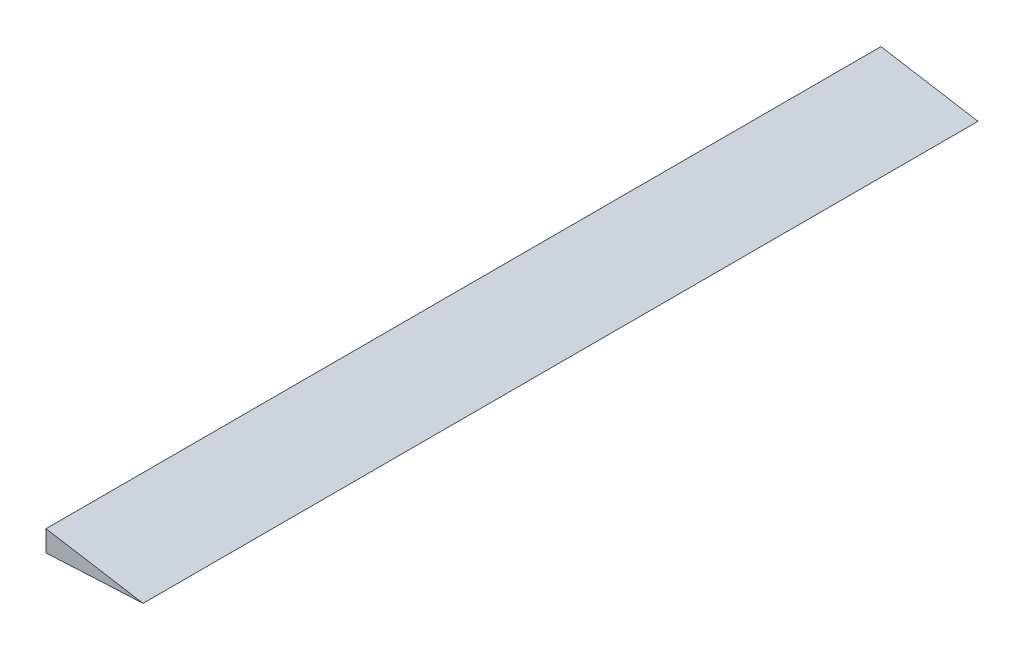
SolidWorks part; units mm, degrees
material "Balsa"
ref_plane "Front Plane" through (0, 0, 0) normal (0, 0, 1) x (1, 0, 0)
ref_plane "Top Plane" through (0, 0, 0) normal (0, 1, 0) x (1, 0, 0)
ref_plane "Right Plane" through (0, 0, 0) normal (1, 0, 0) x (0, 0, -1)
sketch "Sketch1" plane through (0, 0, 0) normal (0, 0, 1) x (1, 0, 0)
  line L0 (306.8496, -2.5161) -> (306.8496, 8.4499) construction
  line L1 (306.8496, -2.5161) -> (306.8496, 8.4499)
  line L2 (306.8496, 8.4499) -> (357.6496, 0)
  line L3 (306.8496, -2.5161) -> (357.6496, 0)
  spline S0 degree 3 poles (354.9573, 0.0431) (358.3317, -0.0432) (354.9981, 0.2938) (352.3707, 0.8024) (346.1763, 1.8676) (338.7813, 3.2655) (329.3081, 4.8919) (318.2482, 6.6648) (305.5952, 8.6507) (291.564, 10.8193) (276.34, 13.1505) (260.1392, 15.5903) (243.1815, 18.0913) (225.699, 20.6027) (207.9209, 23.0318) (190.087, 25.3152) (172.4086, 27.3328) (155.0467, 28.9096) (138.1258, 29.947) (121.7437, 30.3922) (105.9899, 30.2108) (90.9433, 29.4155) (76.6903, 28.0308) (63.3272, 26.1868) (50.9728, 23.9485) (39.7523, 21.3791) (29.7714, 18.545) (21.1318, 15.5018) (13.8914, 12.3237) (8.1391, 9.1075) (3.8158, 5.9031) (1.1802, 2.9693) (-0.4877, -0.018) (1.2572, -2.9285) (4.805, -4.6528) (9.8754, -6.6365) (16.78, -8.2511) (25.3535, -9.7017) (35.5828, -10.8813) (47.3622, -11.8027) (60.5842, -12.4624) (75.1117, -12.8607) (90.7897, -13.0132) (107.4435, -12.9137) (124.9052, -12.5651) (143.0256, -11.8868) (161.6617, -10.9405) (180.6424, -9.8572) (199.7442, -8.7119) (218.721, -7.5525) (237.3263, -6.4253) (255.3201, -5.3536) (272.4652, -4.367) (288.5372, -3.4753) (303.3148, -2.6922) (316.6121, -2.0207) (328.2104, -1.4385) (338.1246, -0.9102) (345.8395, -0.4061) (352.2525, -0.129) (354.9573, 0.0431) (358.3317, -0.0432) (354.9981, 0.2938) knots -0.015092 -0.006889 -0.001754 0 0.001748 0.006827 0.01488 0.025572 0.038694 0.054171 0.071834 0.091435 0.112685 0.135293 0.158944 0.183315 0.20807 0.232879 0.257399 0.281384 0.304706 0.327241 0.348897 0.369607 0.389308 0.407886 0.425177 0.441027 0.4553 0.467904 0.478752 0.487814 0.49509 0.500617 0.504451 0.507804 0.513091 0.520546 0.530249 0.542214 0.556382 0.572656 0.590895 0.610925 0.632536 0.655496 0.679547 0.704499 0.730211 0.756436 0.782837 0.809062 0.834776 0.859641 0.883338 0.905541 0.925965 0.944326 0.960366 0.973929 0.984908 0.993111 0.998246 1 1.001748 1.006827 1.01488 only from (357.6496, 0) to (357.6496, 0) construction
  spline S1 degree 3 poles (354.9573, 0.0431) (358.3317, -0.0432) (354.9981, 0.2938) (352.3707, 0.8024) (346.1763, 1.8676) (338.7813, 3.2655) (329.3081, 4.8919) (318.2482, 6.6648) (305.5952, 8.6507) (291.564, 10.8193) (276.34, 13.1505) (260.1392, 15.5903) (243.1815, 18.0913) (225.699, 20.6027) (207.9209, 23.0318) (190.087, 25.3152) (172.4086, 27.3328) (155.0467, 28.9096) (138.1258, 29.947) (121.7437, 30.3922) (105.9899, 30.2108) (90.9433, 29.4155) (76.6903, 28.0308) (63.3272, 26.1868) (50.9728, 23.9485) (39.7523, 21.3791) (29.7714, 18.545) (21.1318, 15.5018) (13.8914, 12.3237) (8.1391, 9.1075) (3.8158, 5.9031) (1.1802, 2.9693) (-0.4877, -0.018) (1.2572, -2.9285) (4.805, -4.6528) (9.8754, -6.6365) (16.78, -8.2511) (25.3535, -9.7017) (35.5828, -10.8813) (47.3622, -11.8027) (60.5842, -12.4624) (75.1117, -12.8607) (90.7897, -13.0132) (107.4435, -12.9137) (124.9052, -12.5651) (143.0256, -11.8868) (161.6617, -10.9405) (180.6424, -9.8572) (199.7442, -8.7119) (218.721, -7.5525) (237.3263, -6.4253) (255.3201, -5.3536) (272.4652, -4.367) (288.5372, -3.4753) (303.3148, -2.6922) (316.6121, -2.0207) (328.2104, -1.4385) (338.1246, -0.9102) (345.8395, -0.4061) (352.2525, -0.129) (354.9573, 0.0431) (358.3317, -0.0432) (354.9981, 0.2938) knots -0.015092 -0.006889 -0.001754 0 0.001748 0.006827 0.01488 0.025572 0.038694 0.054171 0.071834 0.091435 0.112685 0.135293 0.158944 0.183315 0.20807 0.232879 0.257399 0.281384 0.304706 0.327241 0.348897 0.369607 0.389308 0.407886 0.425177 0.441027 0.4553 0.467904 0.478752 0.487814 0.49509 0.500617 0.504451 0.507804 0.513091 0.520546 0.530249 0.542214 0.556382 0.572656 0.590895 0.610925 0.632536 0.655496 0.679547 0.704499 0.730211 0.756436 0.782837 0.809062 0.834776 0.859641 0.883338 0.905541 0.925965 0.944326 0.960366 0.973929 0.984908 0.993111 0.998246 1 1.001748 1.006827 1.01488 only from (357.6496, 0) to (357.6496, 0)
sketch "Sketch2" plane through (0, 0, -761.9997) normal (0, 0, -1) x (-1, 0, 0)
  line L0 (-306.8496, -2.5161) -> (-306.8496, 8.4499) construction
  line L1 (-306.8496, -2.5161) -> (-357.6496, 0) construction
  line L2 (-306.8496, 8.4499) -> (-357.6496, 0) construction
  line L3 (-306.8496, -2.5161) -> (-306.8496, 8.4499)
  line L4 (-306.8496, -2.5161) -> (-357.6496, 0)
  line L5 (-306.8496, 8.4499) -> (-357.6496, 0)
extrude "Boss-Extrude2" add sketch "Sketch2" against normal blind 437.0222
